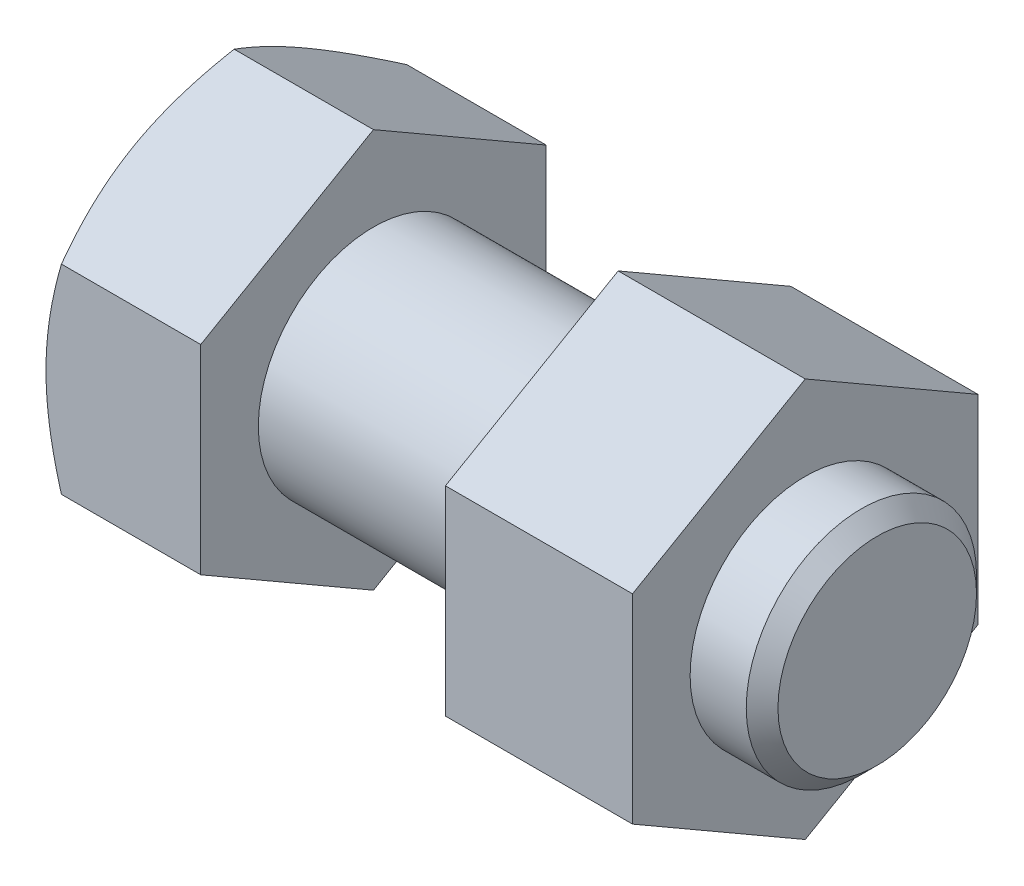
SolidWorks part; units mm, degrees
extrude "BaseHead" add sketch "Sketch1" along normal blind 10.75
sketch "Sketch1" plane through (0, 0, 0) normal (1, 0, 0) x (0, 0, -1)
  line L0 (12, 6.9282) -> (12, -6.9282)
  line L1 (-12, 6.9282) -> (-12, -6.9282)
  line L2 (12, -6.9282) -> (0, -13.8564)
  line L3 (0, -13.8564) -> (-12, -6.9282)
  line L4 (12, 6.9282) -> (0, 13.8564)
  line L5 (0, 13.8564) -> (-12, 6.9282)
  dimension "Width_flats" = 24
  dimension "D2" = 120
  dimension "D3" = 12
  dimension "D4" = 12
  dimension "D5" = 12
material "Dacromet"
ref_plane "Plane1" through (0, 0, 0) normal (0, 0, 1) x (1, 0, 0)
ref_plane "Plane2" through (0, 0, 0) normal (0, 1, 0) x (1, 0, 0)
ref_plane "Plane3" through (0, 0, 0) normal (1, 0, 0) x (0, 0, -1)
sketch "BodySke" plane through (0, 0, 0) normal (0, 0, 1) x (1, 0, 0)
  line L0 (0, 6.9282) -> (0, -6.9282) construction
  line L1 (0, 0) -> (45.75, 0)
  line L2 (0, 0) -> (0, 8)
  line L3 (0, 8) -> (44.6485, 8)
  line L4 (45.75, 0) -> (45.75, 6.8985)
  line L5 (10.75, 13.8564) -> (10.75, 6.9282) construction
  line L6 (45.75, 6.8985) -> (44.6485, 8)
  line L7 (0, 0) -> (96.52, 0) construction
  line L8 (45.75, -6.8985) -> (44.6485, -8) construction
  line L9 (0, -8) -> (44.6485, -8) construction
  line L10 (12.75, 15.24) -> (12.75, -1.27) construction
  line L11 (7.75, 15.24) -> (7.75, -1.27) construction
  line L12 (10.75, 6.9282) -> (10.75, -6.9282) construction
  dimension "Diameter" = 16
revolve "BaseBody" add sketch "BodySke"
cosmetic thread "ThreadCosmetic" [suppressed]
fillet "HeadFillet" [suppressed] radius 0.6
sketch "Sketch3" plane through (0, 0, 0) normal (0, 0, 1) x (1, 0, 0)
  line L0 (0, 12) -> (3.9585, 18.8564)
  line L1 (0, 13.8564) -> (0, 6.9282) construction
  line L2 (3.9585, 18.8564) -> (3.9585, 23.8564)
  line L3 (3.9585, 23.8564) -> (-10, 23.8564)
  line L4 (-10, 23.8564) -> (-10, 12)
  line L5 (-10, 12) -> (0, 12)
  line L6 (0, 0) -> (99.06, 0) construction
  line L7 (10.75, 13.8564) -> (0, 13.8564) construction
  dimension "D1" = 12
  dimension "D2" = 5
  dimension "D3" = 10
  dimension "D4" = 5
  dimension "Head_ch_ang" = 30
revolve "HeadChamfer" cut sketch "Sketch3" angle 360 about L6
sketch "ThdSchSke" plane through (0, 0, 0) normal (0, 0, 1) x (1, 0, 0)
  line L0 (12.75, -6.8985) -> (11.9787, -8)
  line L1 (12.75, -6.8985) -> (13.5213, -8)
  line L2 (13.5213, -8) -> (13.5213, -10)
  line L3 (-3.175, 0) -> (5.1513, 0) construction
  line L5 (13.5213, -10) -> (11.9787, -10)
  line L6 (11.9787, -10) -> (11.9787, -8)
  dimension "Thread_minor" = 13.797
  dimension "Diameter" = 16
  dimension "Start" = 12.75
revolve "ThreadSchematic" [suppressed] cut sketch "ThdSchSke" angle 360 about L3
pattern_linear "ThdSchPat" [suppressed]
ref_plane "Plane4" through (40.75, 0, 0) normal (1, 0, 0) x (0, 0, -1)
sketch "Sketch4" plane through (40.75, 0, 0) normal (1, 0, 0) x (0, 0, -1)
  line L1 (0, 13.8564) -> (-12, 6.9282)
  line L2 (-12, 6.9282) -> (-12, -6.9282)
  line L3 (-12, -6.9282) -> (0, -13.8564)
  line L4 (0, -13.8564) -> (12, -6.9282)
  line L5 (12, -6.9282) -> (12, 6.9282)
  line L6 (12, 6.9282) -> (0, 13.8564)
  circle A0 centre (0, 0) radius 12 construction
extrude "Boss-Extrude1" add sketch "Sketch4" against normal blind 13 separate body
equation "\"D3@Sketch1\" = \"Width_flats@Sketch1\" / 2"
equation "\"D4@Sketch1\" = \"D3@Sketch1\""
equation "\"D5@Sketch1\" = \"D4@Sketch1\""
equation "\"Thread_minor@ThreadCosmetic\" = \"Minor_dia@BodySke\""
equation "\"D1@Sketch3\" = \"Width_flats@Sketch1\" / 2"
equation "' \"D1@Sketch4\" = \"Width_flats@Sketch1\""
equation "\"Thread_length@ThreadCosmetic\" = ((sgn( (\"Length@BodySke\" - \"Advance@BodySke\" ) - \"Thread_nom@BodySke\" )-1)*( (\"Length@BodySke\" - \"Advance@BodySke\" ) - \"Thread_nom@BodySke\" ))/-2+ \"Thread_nom@BodySke\""
equation "\"Thread_minor@ThdSchSke\" = \"Minor_dia@BodySke\""
equation "\"Diameter@ThdSchSke\" = \"Diameter@BodySke\""
equation "\"Overcut@ThdSchSke\" = \"Diameter@BodySke\" * 1.25"
equation "\"Start@ThdSchSke\" = \"Head_ht@BaseHead\" + \"Length@BodySke\" - \"Thread_length@ThreadCosmetic\"  '---Non-countersunk---"
equation "\"Num_threads@ThdSchPat\" = int( \"Thread_length@ThreadCosmetic\" / \"Advance@BodySke\" + 0.999 )  + 1"
equation "\"Advance@ThdSchPat\" = \"Thread_length@ThreadCosmetic\" /  (\"Num_threads@ThdSchPat\" - 1) 'relax it"
equation "\"Num_threads@ThdSchPat\" = \"Num_threads@ThdSchPat\" - sgn( \"Num_threads@ThdSchPat\" - 1) '---chamfered tips only---"
